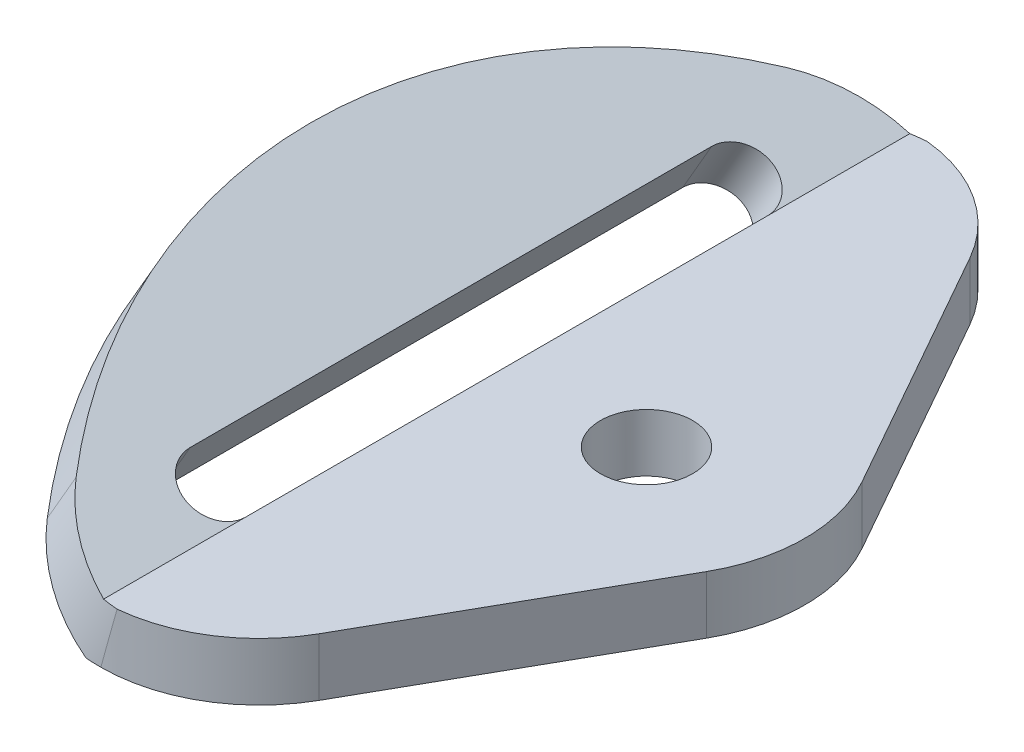
SolidWorks part; units mm, degrees
ref_plane "Front Plane" through (0, 0, 0) normal (0, 0, 1) x (1, 0, 0)
ref_plane "Top Plane" through (0, 0, 0) normal (0, 1, 0) x (1, 0, 0)
ref_plane "Right Plane" through (0, 0, 0) normal (1, 0, 0) x (0, 0, -1)
sketch "Sketch1" plane through (0, 0, 0) normal (0, 0, 1) x (1, 0, 0)
  line L0 (0, 0) -> (27.178, 0)
  line L1 (27.178, 0) -> (27.178, 5.0038)
  line L2 (27.178, 5.0038) -> (1.3408, 5.0038)
  line L3 (0, 0) -> (-18.1476, 10.4775)
  line L4 (-18.1476, 10.4775) -> (-15.6457, 14.8109)
  line L5 (-15.6457, 14.8109) -> (1.3408, 5.0038)
  dimension "D1" = 27.178
  dimension "D2" = 20.955
  dimension "D3" = 5.0038
  dimension "D4" = 30
extrude "Boss-Extrude1" add sketch "Sketch1" along normal mid plane 70.358
sketch "Sketch2" plane through (0, 0, 0) normal (0, -1, 0) x (1, 0, 0)
  line L0 (0, 0) -> (13.462, 0) construction
  line L2 (1.3408, 35.179) -> (53.0152, 35.179)
  line L3 (53.0152, 35.179) -> (53.0152, -35.179)
  line L4 (53.0152, -35.179) -> (1.3408, -35.179)
  line L5 (27.178, 35.179) -> (27.178, -35.179) construction
  line L7 (13.2838, 28.2078) -> (25.405, 6.7448)
  line L8 (13.2838, -28.2078) -> (25.405, -6.7448)
  line L10 (1.3408, 35.179) -> (1.3408, -35.179) construction
  circle A0 centre (13.462, 0) radius 4
  arc A1 (25.405, -6.7448) -> (25.405, 6.7448) centre (13.462, 0) ccw
  arc A2 (1.3408, -35.179) -> (13.2838, -28.2078) centre (1.3408, -21.463) ccw
  arc A3 (13.2838, 28.2078) -> (1.3408, 35.179) centre (1.3408, 21.463) ccw
  dimension "D1" = 8
  dimension "D3" = 13.716
  dimension "D2" = 13.716
extrude "Cut-Extrude2" cut sketch "Sketch2" against normal up to next
sketch "Sketch3" plane through (0, 0, 0) normal (-0.5, -0.866, 0) x (0, 0, 1)
  line L0 (22.606, 4.1348) -> (-22.606, 4.1348) construction
  line L1 (0, 4.1348) -> (0, 0) construction
  line L2 (22.606, 6.9288) -> (-22.606, 6.9288)
  line L3 (22.606, 1.3408) -> (-22.606, 1.3408)
  line L4 (-35.179, -1.1611) -> (35.179, -1.1611) construction
  line L5 (35.179, 20.955) -> (-35.179, 20.955) construction
  line L6 (-35.179, -1.1611) -> (-35.179, 43.0711)
  line L7 (-35.179, 43.0711) -> (35.179, 43.0711)
  line L8 (35.179, 43.0711) -> (35.179, -1.1611)
  line L9 (35.179, 1.3408) -> (-35.179, 1.3408) construction
  arc A0 (22.606, 1.3408) -> (22.606, 6.9288) centre (22.606, 4.1348) ccw
  arc A1 (-22.606, 6.9288) -> (-22.606, 1.3408) centre (-22.606, 4.1348) ccw
  arc A2 (-30.7732, 8.9111) -> (-35.179, -1.1611) centre (-21.463, -1.1611) ccw
  arc A3 (30.7732, 8.9111) -> (-30.7732, 8.9111) centre (0, -24.3809) ccw
  arc A4 (35.179, -1.1611) -> (30.7732, 8.9111) centre (21.463, -1.1611) ccw
  dimension "D1" = 50.8
  dimension "D4" = 13.716
  dimension "D2" = 5.588
extrude "Cut-Extrude3" cut sketch "Sketch3" against normal up to next
